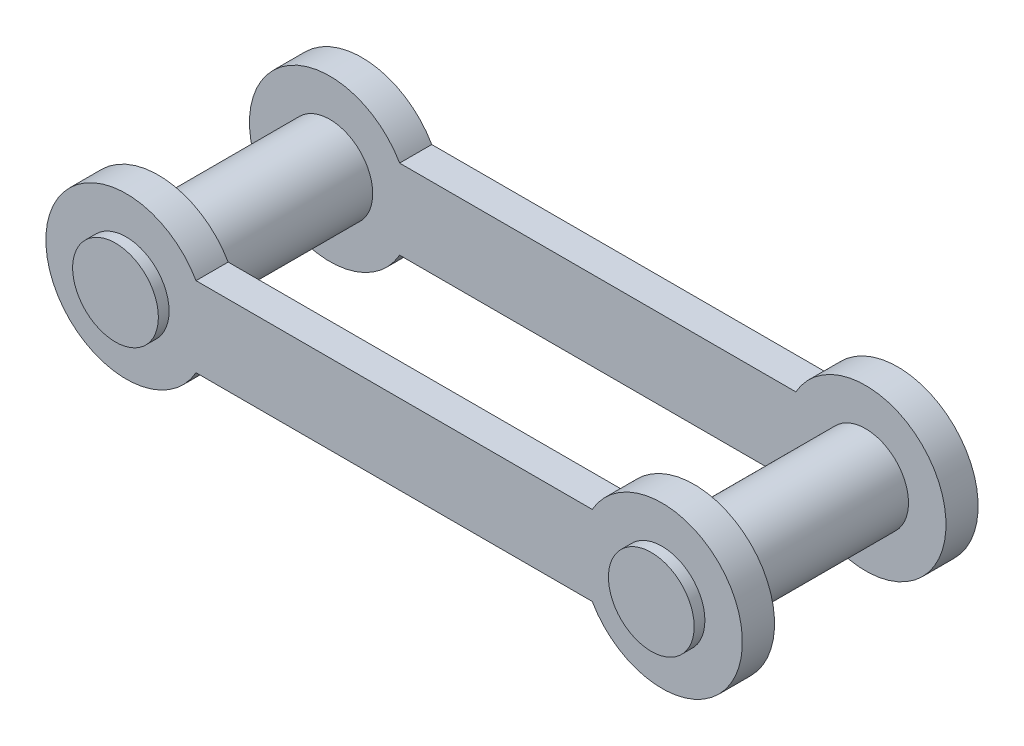
SolidWorks part; units mm, degrees
ref_plane "前视基准面" through (0, 0, 0) normal (0, 0, 1) x (1, 0, 0)
ref_plane "上视基准面" through (0, 0, 0) normal (0, 1, 0) x (1, 0, 0)
ref_plane "右视基准面" through (0, 0, 0) normal (1, 0, 0) x (0, 0, -1)
sketch "草图1" plane through (0, 0, 0) normal (0, 0, 1) x (1, 0, 0)
  line L0 (11.9608, 1.7358) -> (11.9608, 2.5566) construction
  line L1 (11.9608, 2.5566) -> (11.9608, 1.0742) construction
  line L2 (11.9608, 1.7358) -> (-4.1648, 1.7358) construction
  line L3 (-4.1648, 1.7358) -> (-1.5737, 1.7358) construction
  line L4 (-6.5266, 5.4554) -> (30.4481, 5.4554)
  line L5 (-6.5266, -1.9838) -> (30.4481, -1.9838)
  arc A0 (-6.5266, 5.4554) -> (-6.5266, -1.9838) centre (-13.0392, 1.7358) ccw
  circle A1 centre (-13.0392, 1.7358) radius 4
  circle A2 centre (36.9608, 1.7358) radius 4
  arc A3 (30.4481, 5.4554) -> (30.4481, -1.9838) centre (36.9608, 1.7358) cw
  dimension "D2" = 15
  dimension "D3" = 8
  dimension "D1" = 25
extrude "凸台-拉伸1" add sketch "草图1" along normal blind 3
sketch "草图2" plane through (0, 0, 3) normal (0, 0, 1) x (1, 0, 0)
  circle A0 centre (-13.0392, 1.7358) radius 4 construction
  circle A1 centre (36.9608, 1.7358) radius 4 construction
  circle A2 centre (-13.0392, 1.7358) radius 4
  circle A3 centre (36.9608, 1.7358) radius 4
extrude "凸台-拉伸2" add sketch "草图2" along normal blind 20 and the other way blind 4
ref_plane "基准面1" through (0, 0, 11) normal (0, 0, -1) x (-1, 0, 0)
mirror "镜向1" about plane through (0, 0, 11) normal (0, 0, -1) of "凸台-拉伸1"
